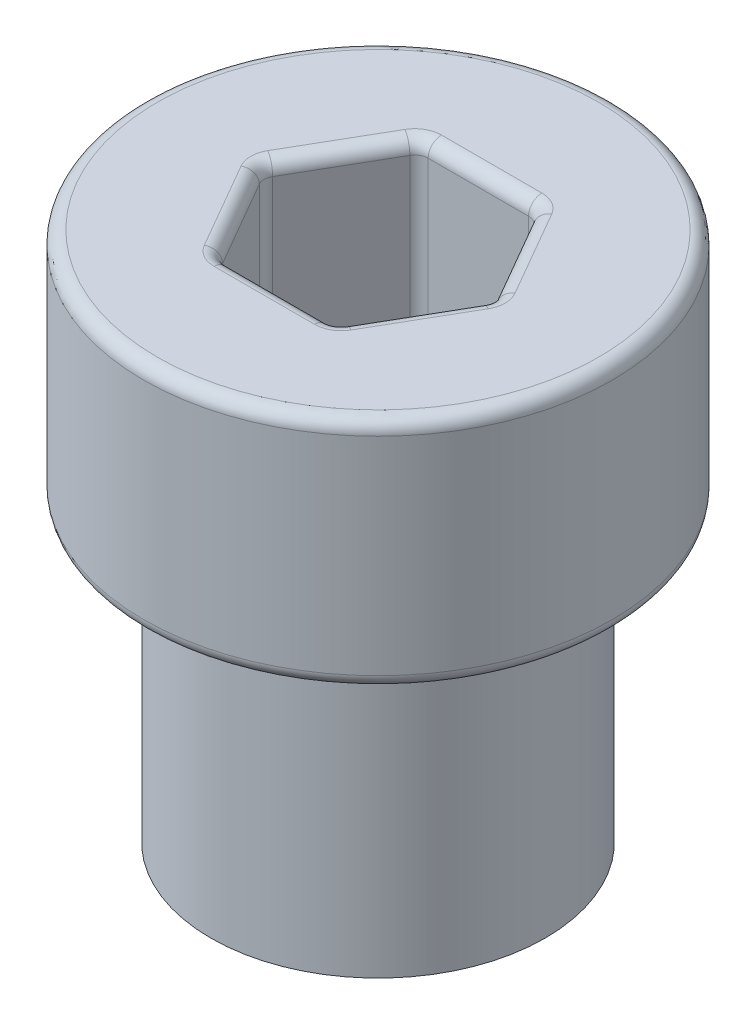
SolidWorks part; units mm, degrees
material "201 Annealed Stainless Steel (SS)"
ref_plane "Front Plane" through (0, 0, 0) normal (0, 0, 1) x (1, 0, 0)
ref_plane "Top Plane" through (0, 0, 0) normal (0, 1, 0) x (1, 0, 0)
ref_plane "Right Plane" through (0, 0, 0) normal (1, 0, 0) x (0, 0, -1)
sketch "Master Sketch" plane through (0, 0, 0) normal (0, 1, 0) x (1, 0, 0)
  line L1 (0.866, 1.5) -> (-0.866, 1.5)
  line L2 (-0.866, 1.5) -> (-1.7321, 0)
  line L3 (-1.7321, 0) -> (-0.866, -1.5)
  line L4 (-0.866, -1.5) -> (0.866, -1.5)
  line L5 (0.866, -1.5) -> (1.7321, 0)
  line L6 (1.7321, 0) -> (0.866, 1.5)
  circle A0 centre (0, 0) radius 3.5
  circle A1 centre (0, 0) radius 1.5 construction
  circle A2 centre (0, 0) radius 2.5
  dimension "D1" = 7
  dimension "D2" = 3
  dimension "D3" = 5
sketch "Head Sketch" plane through (0, 0, 0) normal (0, 1, 0) x (1, 0, 0)
  line L0 (-0.866, 1.5) -> (-1.7321, 0) construction
  line L1 (-0.866, 1.5) -> (-1.7321, 0)
  line L2 (-1.7321, 0) -> (-0.866, -1.5) construction
  line L3 (-0.866, -1.5) -> (0.866, -1.5) construction
  line L4 (0.866, -1.5) -> (1.7321, 0) construction
  line L5 (0.866, 1.5) -> (-0.866, 1.5) construction
  line L6 (1.7321, 0) -> (0.866, 1.5) construction
  line L7 (-1.7321, 0) -> (-0.866, -1.5)
  line L8 (-0.866, -1.5) -> (0.866, -1.5)
  line L9 (0.866, -1.5) -> (1.7321, 0)
  line L10 (0.866, 1.5) -> (-0.866, 1.5)
  line L11 (1.7321, 0) -> (0.866, 1.5)
  circle A0 centre (0, 0) radius 3.5 construction
  circle A1 centre (0, 0) radius 3.5
extrude "Head" add sketch "Head Sketch" along normal blind 3.5
sketch "Threaded Section Stub Sketch" plane through (0, 0, 0) normal (0, 1, 0) x (1, 0, 0)
  circle A0 centre (0, 0) radius 2.5 construction
  circle A1 centre (0, 0) radius 2.5
extrude "Threaded Section" add sketch "Threaded Section Stub Sketch" against normal blind 5
cosmetic thread "Cosmetic Thread1" parameters "D2"=4.11
fillet "Cosmetic Fillets" radius 0.2 20 edges at (0, 0, 3.5) (0, 3.5, 3.5) (1.299, 3.5, -0.75) (0, 3.5, -1.5) (0.866, 1.75, -1.5) (-1.299, 3.5, -0.75) (-0.866, 1.75, -1.5) (-1.299, 3.5, 0.75) (-1.7321, 1.75, 0) (1.7321, 1.75, 0) (1.299, 3.5, 0.75) (0.866, 1.75, 1.5) (0, 3.5, 1.5) (-0.866, 1.75, 1.5) (1.299, 0, 0.75) (0, 0, 1.5) (-1.299, 0, 0.75) (-1.299, 0, -0.75) (0, 0, -1.5) (1.299, 0, -0.75)
chamfer "Bottom Chamfer" distance 1 angle 30 1 edges at (0, -5, 2.5)
